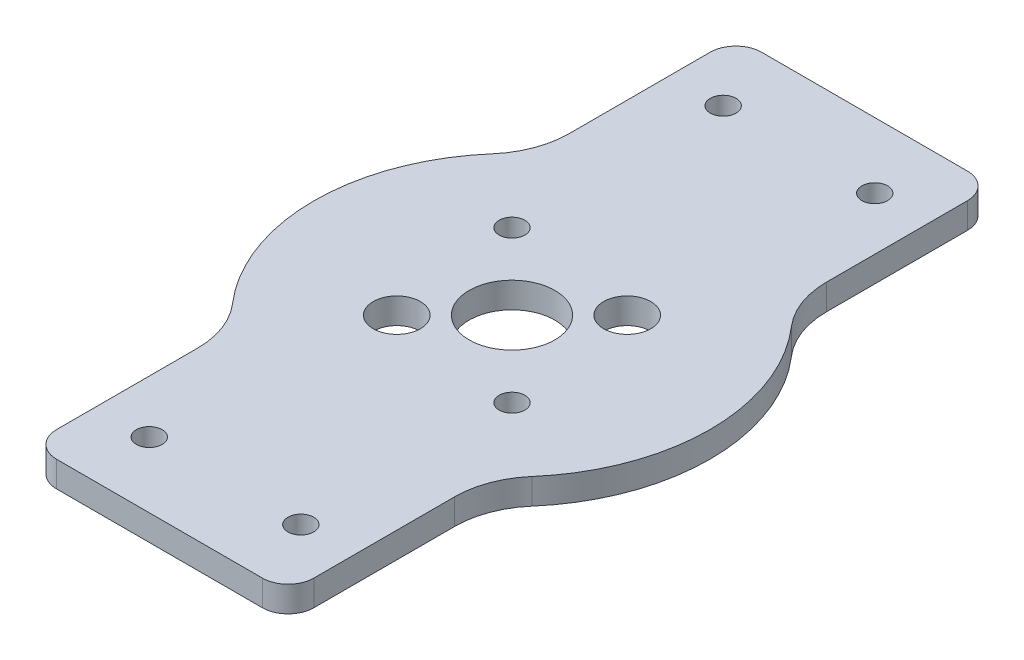
SolidWorks part; units mm, degrees
ref_plane "Front Plane" through (0, 0, 0) normal (0, 0, 1) x (1, 0, 0)
ref_plane "Top Plane" through (0, 0, 0) normal (0, 1, 0) x (1, 0, 0)
ref_plane "Right Plane" through (0, 0, 0) normal (1, 0, 0) x (0, 0, -1)
sketch "Sketch1" plane through (0, 0, 0) normal (0, 1, 0) x (1, 0, 0)
  line L0 (0, 33.4628) -> (0, -42.1291) construction
  line L1 (-39.1744, 0) -> (52.4466, 0) construction
  line L2 (-23.1, -23.1) -> (23.1, -23.1) construction
  line L3 (23.1, -23.1) -> (23.1, 23.1) construction
  line L4 (23.1, 23.1) -> (-23.1, 23.1) construction
  line L5 (-23.1, 23.1) -> (-23.1, -23.1) construction
  line L6 (-23.1, -23.1) -> (23.1, 23.1) construction
  line L7 (-23.1, 23.1) -> (23.1, -23.1) construction
  line L8 (-15, 21.6935) -> (-15, 38.108)
  line L9 (6.5, -42.6342) -> (-6.5, -42.6342) construction
  line L10 (6.5, -42.6342) -> (6.5, 42.6342) construction
  line L11 (6.5, 42.6342) -> (-6.5, 42.6342) construction
  line L12 (-6.5, -42.6342) -> (-6.5, 42.6342) construction
  line L13 (6.5, -42.6342) -> (-6.5, 42.6342) construction
  line L14 (6.5, 42.6342) -> (-6.5, -42.6342) construction
  line L15 (-15, -41.108) -> (15, -41.108) construction
  line L16 (-15, -41.108) -> (-15, 41.108) construction
  line L17 (-15, 41.108) -> (15, 41.108) construction
  line L18 (15, -41.108) -> (15, 41.108) construction
  line L19 (-15, -41.108) -> (15, 41.108) construction
  line L20 (-15, 41.108) -> (15, -41.108) construction
  line L21 (-12, 41.108) -> (12, 41.108)
  line L22 (15, 38.108) -> (15, 21.6935)
  line L23 (-15, -21.6935) -> (-15, -38.108)
  line L24 (-12, -41.108) -> (12, -41.108)
  line L25 (15, -38.108) -> (15, -21.6935)
  circle A0 centre (0, 0) radius 23.1 construction
  circle A1 centre (0, 0) radius 9.5 construction
  circle A2 centre (0, 0) radius 12.5 construction
  circle A3 centre (-8.8388, 8.8388) radius 1.5
  circle A4 centre (8.8388, -8.8388) radius 1.5
  circle A5 centre (6.7175, 6.7175) radius 2.75
  circle A6 centre (-6.7175, -6.7175) radius 2.75
  circle A7 centre (0, 0) radius 5
  arc A8 (-17.4471, 15.1396) -> (-17.4471, -15.1396) centre (0, 0) ccw
  arc A9 (17.4471, 15.1396) -> (17.4471, -15.1396) centre (0, 0) cw
  arc A10 (15, 21.6935) -> (17.4471, 15.1396) centre (25, 21.6935) ccw
  arc A11 (-17.4471, 15.1396) -> (-15, 21.6935) centre (-25, 21.6935) ccw
  arc A12 (-15, -21.6935) -> (-17.4471, -15.1396) centre (-25, -21.6935) ccw
  arc A13 (15, -21.6935) -> (17.4471, -15.1396) centre (25, -21.6935) cw
  circle A14 centre (-8.8388, 33.4628) radius 1.5
  circle A15 centre (8.8388, 33.4628) radius 1.5
  circle A16 centre (8.8388, -33.4628) radius 1.5
  circle A17 centre (-8.8388, -33.4628) radius 1.5
  arc A18 (-15, -38.108) -> (-12, -41.108) centre (-12, -38.108) ccw
  arc A19 (12, -41.108) -> (15, -38.108) centre (12, -38.108) ccw
  arc A20 (-15, 38.108) -> (-12, 41.108) centre (-12, 38.108) cw
  arc A21 (12, 41.108) -> (15, 38.108) centre (12, 38.108) cw
  point P38 (15, 17.5673)
  point P41 (-15, 17.5673)
  dimension "D1" = 46.2
  dimension "D3" = 10
  dimension "D4" = 10
  dimension "D5" = 10
  dimension "D6" = 10
  dimension "D7" = 3
  dimension "D2" = 13
extrude "Boss-Extrude1" add sketch "Sketch1" along normal blind 3
